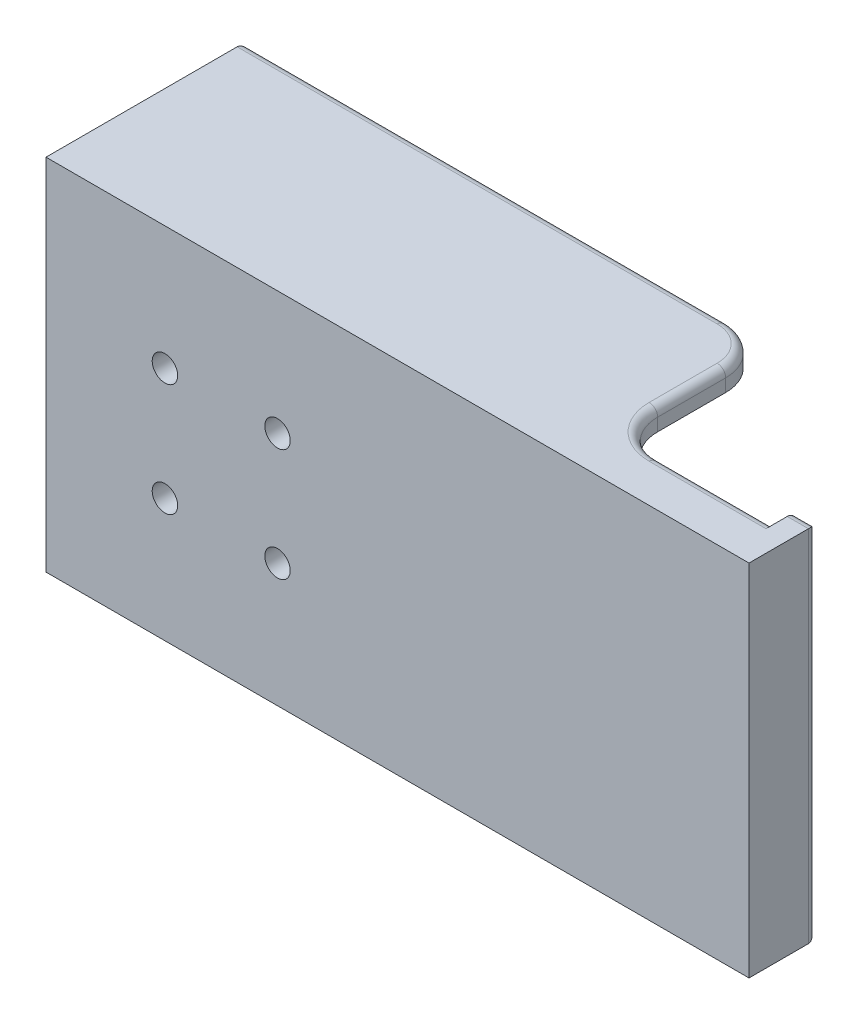
SolidWorks part; units mm, degrees
ref_plane "Alzado" through (0, 0, 0) normal (0, 0, 1) x (1, 0, 0)
ref_plane "Planta" through (0, 0, 0) normal (0, 1, 0) x (1, 0, 0)
ref_plane "Vista lateral" through (0, 0, 0) normal (1, 0, 0) x (0, 0, -1)
sketch "Croquis1" plane through (0, 0, 0) normal (0, 0, 1) x (1, 0, 0)
  line L1 (-59, -42.3) -> (59, -42.3)
  line L2 (-59, -42.3) -> (-59, 42.3)
  line L3 (-59, 42.3) -> (59, 42.3)
  line L4 (59, -42.3) -> (59, 42.3)
  line L5 (-59, -42.3) -> (59, 42.3) construction
  line L6 (-59, 42.3) -> (59, -42.3) construction
  point P0 (0, 0)
  dimension "D1" = 84.6
extrude "Saliente-Extruir1" add sketch "Croquis1" along normal blind 36
sketch "Croquis2" plane through (59, 0, 0) normal (1, 0, 0) x (0, 0, -1)
  line L1 (-36, 42.3) -> (0, 42.3) construction
  line L5 (0, -37.3) -> (0, 37.3)
  line L6 (0, -42.3) -> (0, 42.3) construction
  line L7 (0, 37.3) -> (-36, 37.3)
  line L8 (-36, -42.3) -> (-36, 42.3) construction
  line L9 (-36, 37.3) -> (-36, -37.3)
  line L10 (-36, -37.3) -> (0, -37.3)
  point P5 (0, 0)
  dimension "D1" = 5
extrude "Cortar-Extruir1" cut sketch "Croquis2" against normal blind 120
sketch "Croquis6" plane through (0, -42.3, 0) normal (0, -1, 0) x (1, 0, 0)
  line L0 (-59, 36) -> (59, 36) construction
  line L1 (-59, 0) -> (-59, 36)
  line L2 (-59, 36) -> (0, 36)
  arc A0 (-59, 0) -> (0, 36) centre (8.6236, -44.4803) cw
  point P9 (8.6236, -44.4803)
extrude "Cortar-Extruir3" cut sketch "Croquis6" against normal through all
sketch "Croquis7" plane through (0, 42.3, 0) normal (0, -1, 0) x (1, 0, 0)
  line L1 (59, 36) -> (59, 34)
  line L2 (59, 36) -> (59, 0) construction
  line L8 (-59, 0) -> (-59, 36)
  line L9 (-59, 36) -> (0, 36)
  arc A0 (-59, 0) -> (0, 36) centre (8.6236, -44.4803) cw
extrude "Saliente-Extruir2" add sketch "Croquis7" along normal through all separate body contours L9 A0 L8
sketch "Croquis8" plane through (0, 0, 36) normal (0, 0, 1) x (1, 0, 0)
  line L0 (-59, 42.3) -> (-59, -42.3)
  line L1 (-59, -42.3) -> (101.5, -42.3)
  line L2 (101.5, -42.3) -> (101.5, 42.3)
  line L3 (101.5, 42.3) -> (-59, 42.3)
  dimension "D1" = 160.5
extrude "Saliente-Extruir3" add sketch "Croquis8" along normal blind 5
sketch "Croquis9" plane through (-59, 0, 0) normal (-1, 0, 0) x (0, 0, 1)
  line L0 (0, 42.3) -> (41, 42.3)
  line L1 (41, 42.3) -> (41, -42.3)
  line L2 (41, -42.3) -> (0, -42.3)
  line L3 (0, -42.3) -> (0, 42.3)
extrude "Saliente-Extruir4" add sketch "Croquis9" along normal blind 5
sketch "Croquis10" plane through (0, 0, 36) normal (0, 0, -1) x (-1, 0, 0)
  line L0 (-101.5, 42.3) -> (-96.5, 42.3)
  line L1 (-101.5, 42.3) -> (-59, 42.3) construction
  line L2 (-96.5, 42.3) -> (-96.5, -42.3)
  line L3 (-59, -42.3) -> (-101.5, -42.3) construction
  line L4 (-96.5, -42.3) -> (-101.5, -42.3)
  line L5 (-101.5, -42.3) -> (-101.5, 42.3)
extrude "Saliente-Extruir5" add sketch "Croquis10" along normal blind 5
fillet "Redondeo2" radius 10 4 edges at (59, -39.8, 36) (59, -39.8, 0) (59, 39.8, 36) (59, 39.8, 0)
fillet "Redondeo3" radius 2 3 edges at (99, 42.3, 31) (99, -42.3, 31) (101.5, 0, 31)
fillet "Redondeo4" radius 2 11 edges at (82.75, -42.3, 36) (61.9289, -42.3, 33.0711) (59, -42.3, 18) (56.0711, -42.3, 2.9289) (82.75, 42.3, 36) (61.9289, 42.3, 33.0711) (59, 42.3, 18) (56.0711, 42.3, 2.9289) (-7.5, -42.3, 0) (-64, 0, 0) (-7.5, 42.3, 0)
sketch "Croquis18" plane through (0, 0, 41) normal (0, 0, 1) x (1, 0, 0)
  line L0 (-64, 42.3) -> (-64, -42.3)
  line L1 (-64, -42.3) -> (101.5, -42.3)
  line L2 (101.5, -42.3) -> (101.5, 42.3)
  line L3 (101.5, -42.3) -> (101.5, 42.3) construction
  line L4 (101.5, 42.3) -> (-64, 42.3)
extrude "Saliente-Extruir9" add sketch "Croquis18" along normal blind 6
sketch "Croquis11" plane through (0, 0, 47) normal (0, 0, 1) x (1, 0, 0)
  line L0 (-64, 42.3) -> (-64, -42.3) construction
  line L2 (-36, 13.25) -> (-9.5, 13.25) construction
  line L3 (-36, -13.25) -> (-36, 13.25) construction
  line L4 (-9.5, 13.25) -> (-9.5, -13.25) construction
  line L5 (-36, -13.25) -> (-9.5, -13.25) construction
  line L7 (-36, 0) -> (-64, 0) construction
  circle A0 centre (-36, 13.25) radius 6
  circle A1 centre (-9.5, 13.25) radius 6
  circle A2 centre (-9.5, -13.25) radius 6
  circle A3 centre (-36, -13.25) radius 6
  point P8 (-36, 0)
  dimension "12" = 12
  dimension "D2" = 12
  dimension "D3" = 12
  dimension "D4" = 12
  dimension "D5" = 26.5
extrude "Cortar-Extruir6" cut sketch "Croquis11" against normal through all and the other way through all
sketch "Croquis16" plane through (0, 0, 47) normal (0, 0, 1) x (1, 0, 0)
  circle A5 centre (-9.5, 13.25) radius 6
  circle A7 centre (-36, -13.25) radius 6
  circle A8 centre (-9.5, -13.25) radius 6
  circle A9 centre (-36, 13.25) radius 6
extrude "Saliente-Extruir8" add sketch "Croquis16" against normal blind 5
sketch "Croquis17" plane through (0, 0, 47) normal (0, 0, 1) x (1, 0, 0)
  circle A0 centre (-9.5, 13.25) radius 3
  circle A1 centre (-36, 13.25) radius 3
  circle A2 centre (-9.5, -13.25) radius 3
  circle A3 centre (-36, -13.25) radius 3
  dimension "D1" = 6
  dimension "D2" = 6
  dimension "D3" = 6
  dimension "D4" = 6
extrude "Cortar-Extruir7" cut sketch "Croquis17" against normal through all
